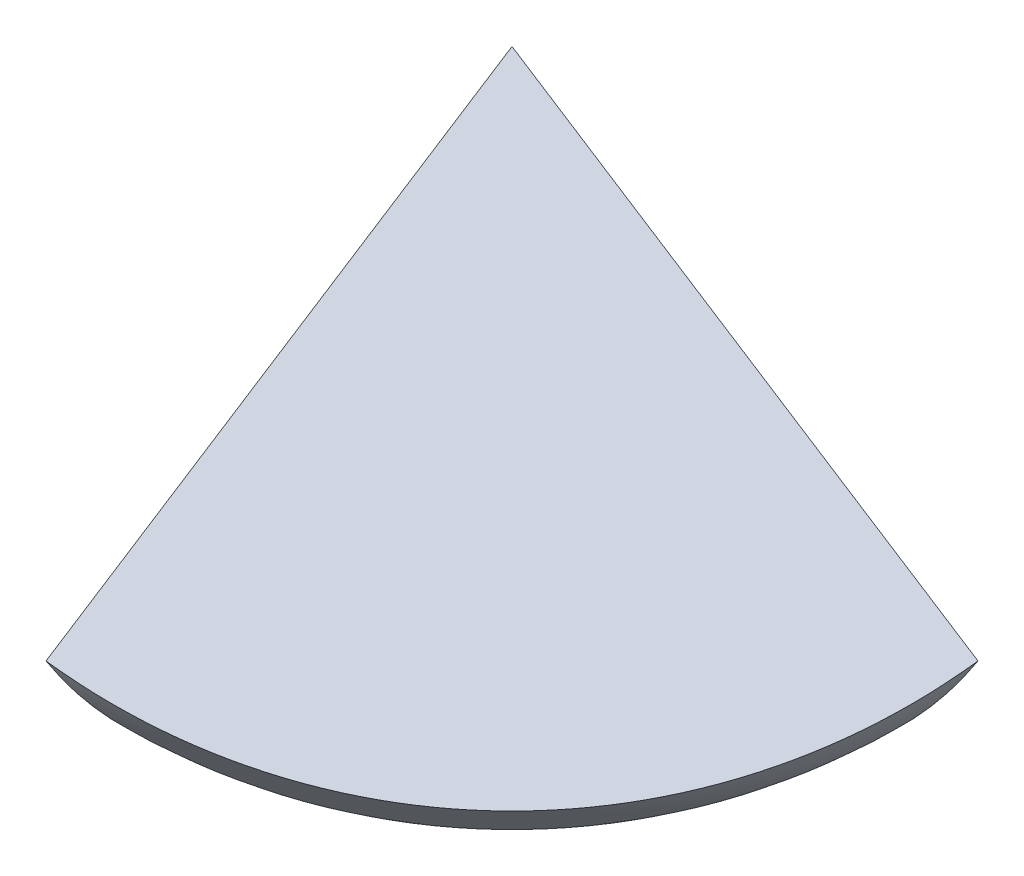
SolidWorks part; units mm, degrees
ref_plane "前视基准面" through (0, 0, 0) normal (0, 0, 1) x (1, 0, 0)
ref_plane "上视基准面" through (0, 0, 0) normal (0, 1, 0) x (1, 0, 0)
ref_plane "右视基准面" through (0, 0, 0) normal (1, 0, 0) x (0, 0, -1)
sketch "草图1" plane through (0, 0, 0) normal (0, 0, 1) x (1, 0, 0)
  line L0 (0, 0) -> (0, 50000) construction
  line L1 (0, 0) -> (0, -150)
  line L2 (0, 0) -> (126.2266, -81.036)
  arc A0 (0, -150) -> (126.2266, -81.036) centre (0, 0) ccw
sketch "草图2" plane through (0, 0, 0) normal (1, 0, 0) x (0, 0, -1)
  line L0 (0, 0) -> (0, -150)
  line L1 (0, 0) -> (0, -150) construction
  line L2 (0, -200000) -> (0, 250000) construction
  line L3 (-126.2266, -81.036) -> (0, 0)
  arc A0 (0, -150) -> (-126.2266, -81.036) centre (0, 0) cw
ref_plane "基准面1" through (0, 0, 0) normal (-0.4753, -0.7404, -0.4753) x (-0.8798, 0.4, 0.2568)
sketch "草图3" plane through (0, 0, 0) normal (-0.4753, -0.7404, -0.4753) x (-0.8798, 0.4, 0.2568)
  line L0 (0, 0) -> (-143.4692, -43.7789) construction
  line L1 (0, -150) -> (0, 0)
  line L2 (0, 0) -> (-143.4692, -43.7789)
  arc A0 (0, -150) -> (-143.4692, -43.7789) centre (0, 0) cw
revolve "旋转2" add sketch "草图1" angle 90 about L0
extrude "切除-拉伸2" cut sketch "草图3" against normal through all
